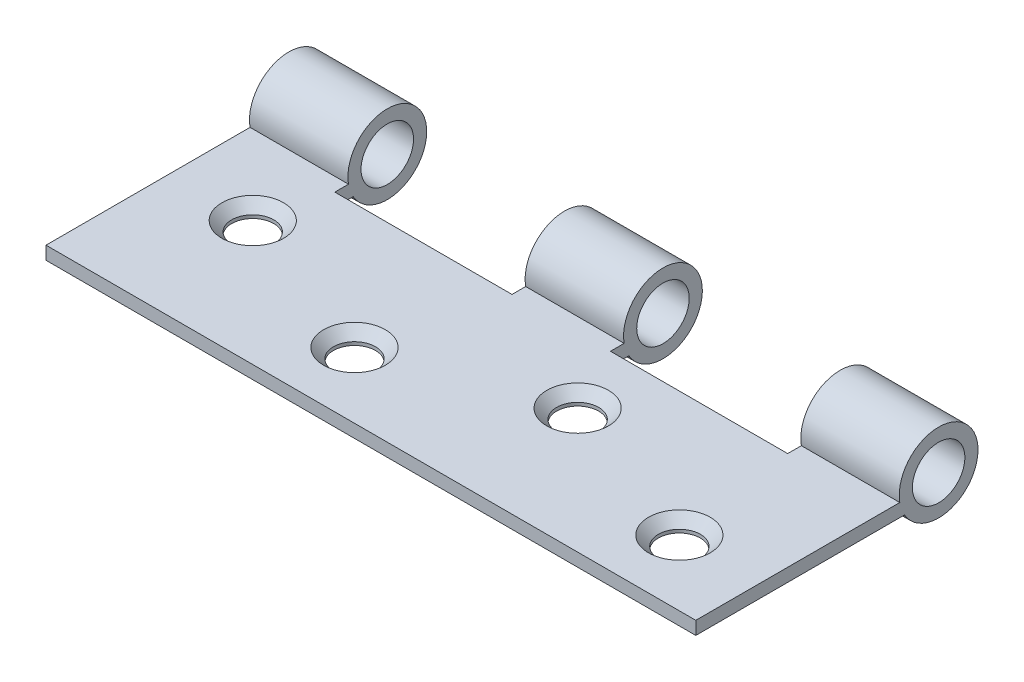
SolidWorks part; units mm, degrees
ref_plane "Front" through (0, 0, 0) normal (0, 0, 1) x (1, 0, 0)
ref_plane "Top" through (0, 0, 0) normal (0, 1, 0) x (1, 0, 0)
ref_plane "Right" through (0, 0, 0) normal (1, 0, 0) x (0, 0, -1)
sketch "草图1" plane through (0, 0, 0) normal (1, 0, 0) x (0, 0, -1)
  circle A0 centre (0, 0) radius 4
  circle A1 centre (0, 0) radius 6
  dimension "D1" = 12
  dimension "D2" = 8
extrude "凸台-拉伸1" add sketch "草图1" along normal blind 99
sketch "草图2" plane through (0, 0, 0) normal (0, 0, 1) x (1, 0, 0)
  line L0 (0, -1) -> (0, -3)
  line L1 (99, -6) -> (99, 6) construction
  line L2 (0, -1) -> (99, -1)
  line L3 (0, 6) -> (0, -6) construction
  line L4 (99, -1) -> (99, -3)
  line L5 (99, -3) -> (0, -3)
  dimension "D1" = 2
  dimension "D2" = 1
extrude "凸台-拉伸2" add sketch "草图2" along normal blind 37
sketch "草图3" plane through (0, 0, 0) normal (-1, 0, 0) x (0, 0, 1)
  circle A0 centre (0, 0) radius 4
extrude "切除-拉伸1" cut sketch "草图3" against normal through all
sketch "草图4" plane through (0, -1, 0) normal (0, 1, 0) x (1, 0, 0)
  line L0 (15, 6) -> (15, -8)
  line L1 (99, 6) -> (0, 6) construction
  line L2 (15, -8) -> (42, -8)
  line L3 (42, -8) -> (42, 6)
  line L4 (99, 6) -> (0, 6) construction
  line L5 (42, 6) -> (15, 6)
  line L6 (0, 6) -> (0, -6) construction
  line L9 (84, 6) -> (84, -8)
  line L10 (57, 6) -> (84, 6)
  line L11 (57, -8) -> (57, 6)
  line L12 (84, -8) -> (57, -8)
  dimension "D1" = 14
  dimension "D2" = 27
  dimension "D3" = 15
extrude "切除-拉伸2" cut sketch "草图4" against normal through all both and the other way through all
sketch "草图7" plane through (0, -3, 0) normal (0, -1, 0) x (1, 0, 0)
  line L0 (0, 37) -> (0, 5.9161) construction
  line L1 (99, 37) -> (0, 37) construction
  circle A8 centre (12.5, 18) radius 3.2
  circle A9 centre (37, 27) radius 3.2
  circle A10 centre (62, 18) radius 3.2
  circle A11 centre (86.5, 27) radius 3.2
  dimension "D2" = 6.4
  dimension "D3" = 6.4
  dimension "D4" = 6.4
  dimension "D5" = 6.4
  dimension "D6" = 19
  dimension "D7" = 10
  dimension "D8" = 37
  dimension "D9" = 19
  dimension "D10" = 62
  dimension "D11" = 10
  dimension "D12" = 86.5
  dimension "D1" = 12.5
extrude "切除-拉伸8" cut sketch "草图7" against normal blind 37
chamfer "倒角1" distance 1.5 angle 45 4 edges at (86.5, -1, 23.8) (62, -1, 14.8) (37, -1, 23.8) (12.5, -1, 14.8)
